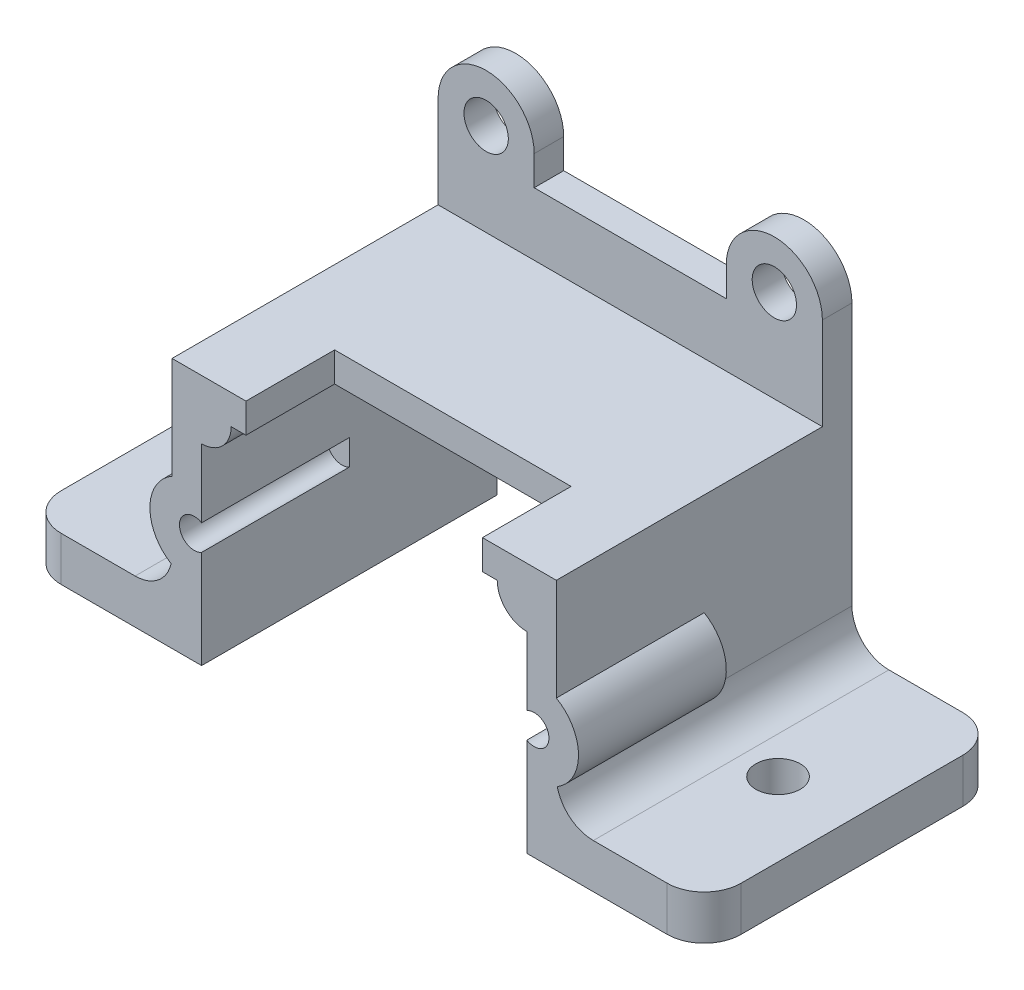
SolidWorks part; units mm, degrees
ref_plane "前视基准面" through (0, 0, 0) normal (0, 0, 1) x (1, 0, 0)
ref_plane "上视基准面" through (0, 0, 0) normal (0, 1, 0) x (1, 0, 0)
ref_plane "右视基准面" through (0, 0, 0) normal (1, 0, 0) x (0, 0, -1)
sketch "草图1" plane through (0, 0, 0) normal (0, 0, 1) x (1, 0, 0)
  line L0 (-15.0735, 6.6657) -> (10.9265, 6.6657)
  line L1 (-13.0735, 4.6657) -> (8.9265, 4.6657)
  line L2 (-13.0735, 4.6657) -> (-13.0735, -1.9683)
  line L4 (8.9265, 4.6657) -> (8.9265, -1.9683)
  line L5 (10.9265, 6.6657) -> (10.9265, -0.2362)
  line L6 (-13.0735, -3.7003) -> (-13.0735, -10.3343)
  line L7 (8.9265, -3.7003) -> (8.9265, -10.3343)
  line L8 (10.9265, -5.4324) -> (10.9265, -10.3343)
  line L10 (-15.0735, -5.4324) -> (-15.0735, -10.3343)
  line L11 (-15.0735, 6.6657) -> (-15.0735, -0.2362)
  line L12 (-13.0735, -10.3343) -> (-15.0735, -10.3343)
  line L13 (8.9265, -10.3343) -> (10.9265, -10.3343)
  line L15 (-15.0735, -5.4324) -> (-15.0735, -12.3343) construction
  line L16 (-13.0735, -10.3343) -> (8.9265, -10.3343) construction
  line L17 (-15.0735, -12.3343) -> (10.9265, -12.3343) construction
  line L18 (10.9265, -5.4324) -> (10.9265, -12.3343) construction
  arc A0 (8.9265, -3.7003) -> (8.9265, -1.9683) centre (9.4265, -2.8343) ccw
  arc A1 (-13.0735, -1.9683) -> (-13.0735, -3.7003) centre (-13.5735, -2.8343) ccw
  arc A2 (10.9265, -5.4324) -> (10.9265, -0.2362) centre (9.4265, -2.8343) ccw
  arc A3 (-15.0735, -0.2362) -> (-15.0735, -5.4324) centre (-13.5735, -2.8343) ccw
  dimension "D1" = 2
extrude "凸台-拉伸1" add sketch "草图1" along normal blind 20
sketch "草图2" plane through (0, 6.6657, 0) normal (0, 1, 0) x (1, 0, 0)
  line L1 (10.9265, -20) -> (-15.0735, -20) construction
  line L2 (-2.0735, -14) -> (-10.0735, -14)
  line L3 (-2.0735, -14) -> (5.9265, -14)
  line L4 (5.9265, -14) -> (5.9265, -20)
  line L5 (5.9265, -20) -> (-10.0735, -20)
  line L6 (-10.0735, -20) -> (-10.0735, -14)
extrude "切除-拉伸1" cut sketch "草图2" against normal blind 20
sketch "草图3" plane through (0, 0, 20) normal (0, 0, 1) x (1, 0, 0)
  line L0 (-13.0735, 4.6657) -> (-13.0735, 2.6657)
  line L1 (-13.0735, 4.6657) -> (-11.0735, 4.6657)
  line L2 (8.9265, 4.6657) -> (8.9265, 2.6657)
  line L3 (8.9265, 4.6657) -> (6.9265, 4.6657)
  arc A0 (-13.0735, 2.6657) -> (-11.0735, 4.6657) centre (-13.0735, 4.6657) ccw
  arc A1 (6.9265, 4.6657) -> (8.9265, 2.6657) centre (8.9265, 4.6657) ccw
extrude "凸台-拉伸2" add sketch "草图3" against normal blind 12.5
sketch "草图4" plane through (0, 0, 0) normal (0, 0, -1) x (-1, 0, 0)
  line L1 (-10.9265, -0.2362) -> (-15.1348, -0.2362)
  line L2 (-10.9265, -0.2362) -> (-10.9265, -6.0887)
  line L3 (-10.9265, -6.0887) -> (-15.1348, -6.0887)
  line L4 (-15.1348, -0.2362) -> (-15.1348, -6.0887)
  line L5 (15.0735, -0.2362) -> (21.8834, -0.2362)
  line L6 (15.0735, -0.2362) -> (15.0735, -5.8399)
  line L7 (15.0735, -5.8399) -> (21.8834, -5.8399)
  line L8 (21.8834, -0.2362) -> (21.8834, -5.8399)
extrude "切除-拉伸2" cut sketch "草图4" against normal blind 10
sketch "草图5" plane through (0, 0, 0) normal (0, 0, -1) x (-1, 0, 0)
  line L0 (-8.9265, -1.9683) -> (-8.9265, -3.7003)
  line L1 (13.0735, -1.9683) -> (13.0735, -3.7003)
  line L10 (-10.9265, 6.6657) -> (-10.9265, -10.3343)
  line L11 (-10.9265, -10.3343) -> (-8.9265, -10.3343)
  line L12 (-8.9265, -10.3343) -> (-8.9265, -3.7003)
  line L13 (-8.9265, -1.9683) -> (-8.9265, 4.6657)
  line L14 (-8.9265, 4.6657) -> (13.0735, 4.6657)
  line L15 (13.0735, 4.6657) -> (13.0735, -1.9683)
  line L16 (13.0735, -3.7003) -> (13.0735, -10.3343)
  line L17 (13.0735, -10.3343) -> (15.0735, -10.3343)
  line L18 (15.0735, -10.3343) -> (15.0735, 6.6657)
  line L19 (15.0735, 6.6657) -> (-10.9265, 6.6657)
  arc A2 (-8.9265, -1.9683) -> (-8.9265, -3.7003) centre (-9.4265, -2.8343) ccw
  arc A3 (13.0735, -3.7003) -> (13.0735, -1.9683) centre (13.5735, -2.8343) ccw
  arc A4 (-8.9265, -1.9683) -> (-8.9265, -3.7003) centre (-9.4265, -2.8343) ccw
  arc A5 (13.0735, -3.7003) -> (13.0735, -1.9683) centre (13.5735, -2.8343) ccw
  dimension "D1" = 0
extrude "凸台-拉伸3" add sketch "草图5" against normal blind 10
sketch "草图6" plane through (0, -10.3343, 0) normal (0, -1, 0) x (1, 0, 0)
  line L1 (10.9265, 0) -> (20.9265, 0)
  line L2 (10.9265, 0) -> (10.9265, 20)
  line L3 (10.9265, 20) -> (20.9265, 20)
  line L4 (20.9265, 0) -> (20.9265, 20)
  line L5 (-15.0735, 0) -> (-25.0735, 0)
  line L6 (-15.0735, 0) -> (-15.0735, 20)
  line L7 (-15.0735, 20) -> (-25.0735, 20)
  line L8 (-25.0735, 0) -> (-25.0735, 20)
extrude "凸台-拉伸4" add sketch "草图6" against normal blind 3
sketch "草图7" plane through (0, -7.3343, 0) normal (0, 1, 0) x (1, 0, 0)
  circle A0 centre (15.9265, -10) radius 1.5
  circle A1 centre (-20.0735, -10) radius 1.5
extrude "切除-拉伸3" cut sketch "草图7" against normal blind 3
fillet "圆角1" radius 2.5 6 edges at (-15.0735, -7.3343, 10) (10.9265, -7.3343, 10) (20.9265, -8.8343, 20) (-25.0735, -8.8343, 20) (20.9265, -8.8343, 0) (-25.0735, -8.8343, 0)
sketch "草图8" plane through (0, 0, 0) normal (0, 0, -1) x (-1, 0, 0)
  line L0 (-4.4265, 10.9157) -> (8.5735, 10.9157)
  line L1 (-10.9265, 6.6657) -> (-10.9265, 12.9157)
  line L2 (-4.4265, 6.6657) -> (8.5735, 6.6657)
  line L3 (15.0735, 6.6657) -> (15.0735, 12.9157)
  line L5 (-4.4265, 12.9157) -> (-4.4265, 10.9157)
  line L6 (-10.9265, 6.6657) -> (15.0735, 6.6657) construction
  line L7 (-4.4265, 6.6657) -> (-10.9265, 6.6657)
  line L8 (8.5735, 12.9157) -> (8.5735, 10.9157)
  line L9 (8.5735, 6.6657) -> (15.0735, 6.6657)
  circle A0 centre (-7.6765, 12.9157) radius 1.5
  arc A1 (-4.4265, 12.9157) -> (-10.9265, 12.9157) centre (-7.6765, 12.9157) ccw
  circle A2 centre (11.8235, 12.9157) radius 1.5
  arc A3 (15.0735, 12.9157) -> (8.5735, 12.9157) centre (11.8235, 12.9157) ccw
extrude "凸台-拉伸5" add sketch "草图8" against normal blind 2
